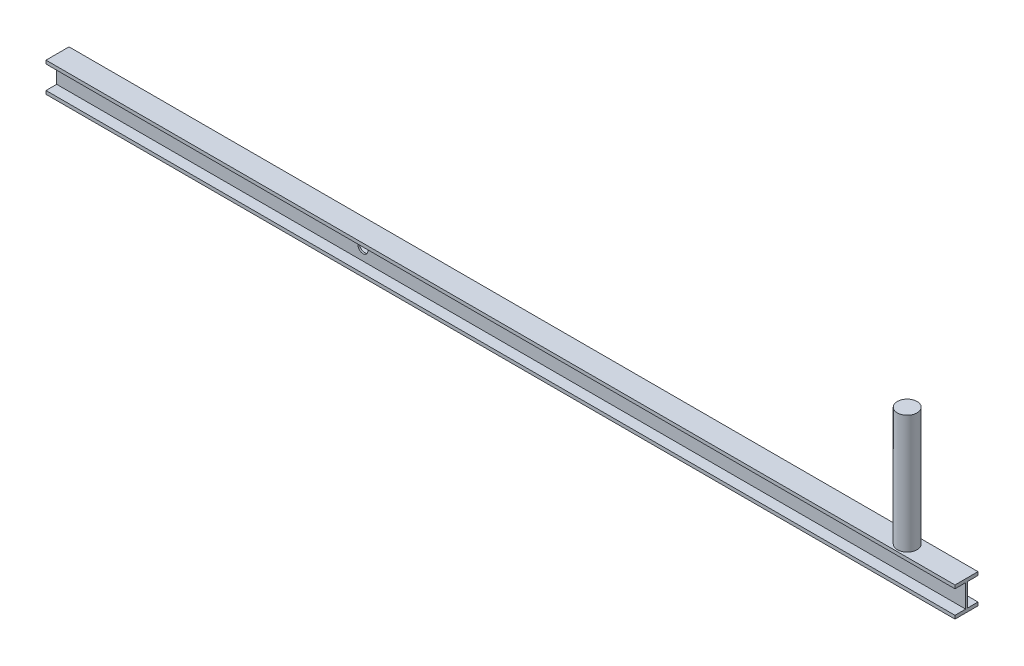
SolidWorks part; units mm, degrees
material "ASTM A36 Steel"
ref_plane "Front Plane" through (0, 0, 0) normal (0, 0, 1) x (1, 0, 0)
ref_plane "Top Plane" through (0, 0, 0) normal (0, 1, 0) x (1, 0, 0)
ref_plane "Right Plane" through (0, 0, 0) normal (1, 0, 0) x (0, 0, -1)
sketch "Sketch1" plane through (0, 0, 0) normal (1, 0, 0) x (0, 0, -1)
  line L0 (59.182, 67.564) -> (59.182, 76.2)
  line L1 (0, 0) -> (59.182, 0)
  line L2 (0, 0) -> (0, 8.636)
  line L3 (0, 76.2) -> (59.182, 76.2)
  line L4 (59.182, 0) -> (59.182, 8.636)
  line L5 (59.182, 67.564) -> (31.75, 67.564)
  line L6 (0, 67.564) -> (0, 76.2)
  line L7 (59.182, 8.636) -> (31.75, 8.636)
  line L8 (31.75, 67.564) -> (31.75, 8.636)
  line L9 (0, 67.564) -> (27.432, 67.564)
  line L11 (0, 8.636) -> (27.432, 8.636)
  line L12 (27.432, 67.564) -> (27.432, 8.636)
  dimension "D1" = 76.2
  dimension "D2" = 59.182
  dimension "D3" = 8.636
  dimension "D4" = 4.318
  dimension "D5" = 8.636
extrude "Boss-Extrude1" add sketch "Sketch1" along normal blind 2336.8
sketch "Sketch3" plane through (0, 76.2, 0) normal (0, 1, 0) x (1, 0, 0)
  line L1 (2336.8, 59.182) -> (2336.8, 0) construction
  line L2 (2184.4, 29.591) -> (2184.4, 0) construction
  line L3 (2336.8, 0) -> (0, 0) construction
  line L4 (2184.4, 29.591) -> (2184.4, 59.182) construction
  line L5 (2336.8, 59.182) -> (0, 59.182) construction
  circle A0 centre (2184.4, 29.591) radius 25.4
  dimension "D1" = 50.8
  dimension "D3" = 152.4
extrude "Boss-Extrude2" add sketch "Sketch3" along normal blind 304.8
sketch "Sketch4" plane through (0, 0, -31.75) normal (0, 0, 1) x (1, 0, 0)
  line L2 (0, 8.636) -> (0, 67.564) construction
  line L3 (787.4, 38.1) -> (787.4, 67.564) construction
  line L4 (2336.8, 67.564) -> (0, 67.564) construction
  line L5 (787.4, 38.1) -> (787.4, 8.636) construction
  line L6 (2336.8, 8.636) -> (0, 8.636) construction
  circle A1 centre (787.4, 38.1) radius 12.7
  dimension "D1" = 25.4
  dimension "D3" = 787.4
extrude "Cut-Extrude2" cut sketch "Sketch4" along normal blind 16.51 contours A1
